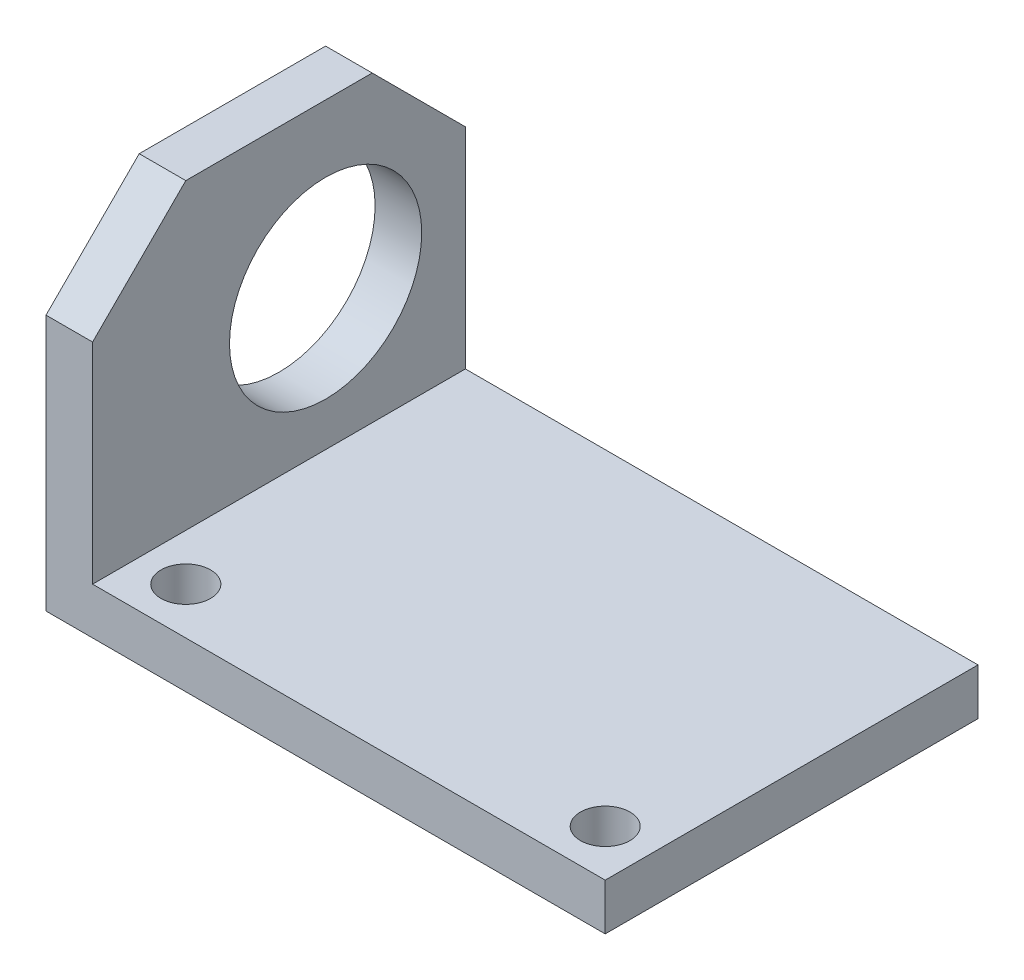
SolidWorks part; units mm, degrees
ref_plane "Front" through (0, 0, 0) normal (0, 0, 1) x (1, 0, 0)
ref_plane "Top" through (0, 0, 0) normal (0, 1, 0) x (1, 0, 0)
ref_plane "Right" through (0, 0, 0) normal (1, 0, 0) x (0, 0, -1)
sketch "Sketch1" plane through (0, 0, 0) normal (0, 0, 1) x (1, 0, 0)
  line L0 (0, 0) -> (76.2, 0)
  line L1 (50, 0) -> (-50, 0) construction
  line L2 (76.2, 0) -> (76.2, 6.35)
  line L3 (76.2, 6.35) -> (6.35, 6.35)
  line L4 (6.35, 6.35) -> (6.35, 47.625)
  line L5 (6.35, 47.625) -> (0, 47.625)
  line L6 (0, -50) -> (0, 50) construction
  line L7 (0, 47.625) -> (0, 0)
  dimension "D1" = 6.35
  dimension "D2" = 76.2
  dimension "D3" = 47.625
extrude "Boss-Extrude1" add sketch "Sketch1" along normal mid plane 50.8
sketch "Sketch2" plane through (0, 0, 0) normal (0, -1, 0) x (1, 0, 0)
  line L0 (76.2, 19.05) -> (69.85, 19.05) construction
  line L2 (69.85, 19.05) -> (12.7, 19.05) construction
  line L3 (76.2, 25.4) -> (76.2, -25.4) construction
  line L4 (0, 25.4) -> (76.2, 25.4) construction
  dimension "D1" = 57.15
  dimension "D2" = 6.35
  dimension "D3" = 6.35
hole_wizard "1/4 Clearance Hole1" positions "Sketch4" profile "Sketch3" hole size "1/4" standard "ANSI Inch" end condition through all
sketch "Sketch4" plane through (0, 0, 0) normal (0, -1, 0) x (-1, 0, 0)
  point P0 (-12.7, -19.05)
  point P3 (-69.85, -19.05)
sketch "Sketch3" plane through (12.7, 0, 19.05) normal (1, 0, 0) x (0, 0, -1)
  line L0 (0, 0) -> (0, 47.625)
  line L1 (0, 47.625) -> (3.3782, 47.625)
  line L2 (3.3782, 47.625) -> (3.3782, 0)
  line L5 (3.3782, 0) -> (0, 0)
  line L11 (0, -6.35) -> (0, 107.95) construction
  dimension "Thru Hole Dia." = 6.7564
  dimension "Thru Hole Depth" = 47.625
sketch "Sketch5" plane through (0, 0, 0) normal (-1, 0, 0) x (0, 0, 1)
  line L0 (-6.35, 0) -> (-6.35, 25.4) construction
  line L2 (-25.4, 47.625) -> (-25.4, 0) construction
  dimension "D1" = 25.4
  dimension "D2" = 19.05
hole_wizard "1 Clearance Hole1" positions "Sketch7" profile "Sketch6" hole size "1" standard "ANSI Inch" end condition through all
sketch "Sketch7" plane through (0, 0, 0) normal (-1, 0, 0) x (0, 0, 1)
  point P0 (-6.35, 25.4)
sketch "Sketch6" plane through (0, 25.4, -6.35) normal (0, 1, 0) x (0, 0, 1)
  line L0 (0, 0) -> (0, 76.2)
  line L1 (0, 76.2) -> (13.0962, 76.2)
  line L2 (13.0962, 76.2) -> (13.0962, 0)
  line L5 (13.0962, 0) -> (0, 0)
  line L11 (0, -6.35) -> (0, 107.95) construction
  dimension "Thru Hole Dia." = 26.1925
  dimension "Thru Hole Depth" = 76.2
chamfer "Chamfer1" distance 12.7 angle 45 2 edges at (3.175, 47.625, -25.4) (3.175, 47.625, 25.4)
